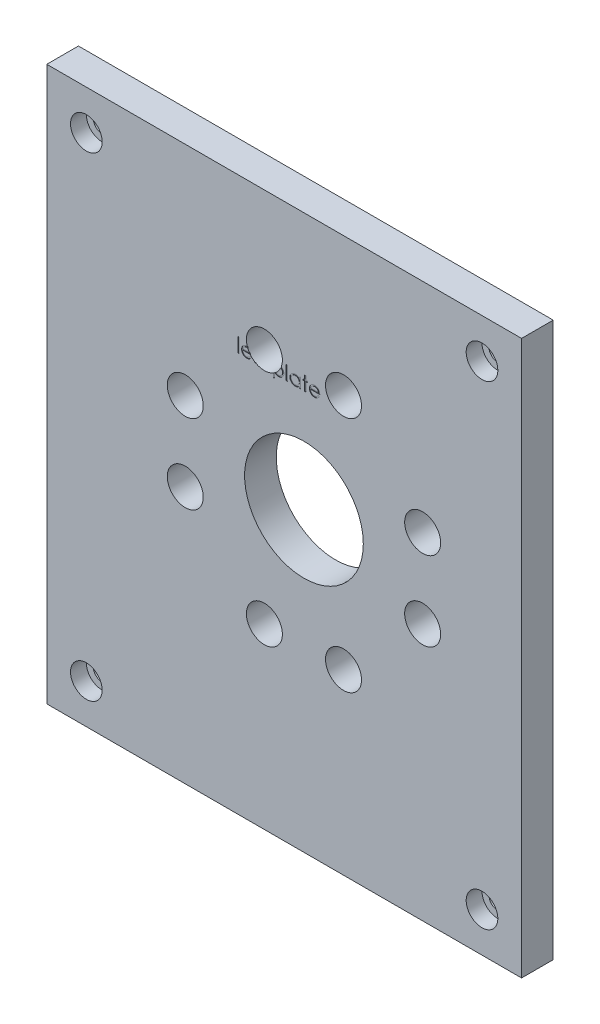
SolidWorks part; units mm, degrees
ref_plane "정면" through (0, 0, 0) normal (0, 0, 1) x (1, 0, 0)
ref_plane "윗면" through (0, 0, 0) normal (0, 1, 0) x (1, 0, 0)
ref_plane "우측면" through (0, 0, 0) normal (1, 0, 0) x (0, 0, -1)
sketch "스케치1" plane through (0, 0, 0) normal (0, 0, 1) x (1, 0, 0)
  line L1 (-60, 70) -> (60, 70)
  line L2 (-60, 70) -> (-60, -70)
  line L3 (-60, -70) -> (60, -70)
  line L4 (60, 70) -> (60, -70)
  line L5 (-60, 70) -> (60, -70) construction
  line L6 (-60, -70) -> (60, 70) construction
  point P0 (0, 0)
  dimension "D1" = 140
  dimension "D2" = 120
extrude "보스-돌출1" add sketch "스케치1" along normal blind 8
hole_wizard "M4 소켓 머리 캡 나사용 카운터보어1" positions "스케치2" profile "스케치3" counterbore size "M4" standard "KS" end condition through all
sketch "스케치2" plane through (0, 0, 8) normal (0, 0, 1) x (1, 0, 0)
  line L0 (60, 70) -> (-60, 70) construction
  line L1 (-60, 70) -> (-60, -70) construction
  line L2 (60, -70) -> (60, 70) construction
  line L3 (-60, -70) -> (60, -70) construction
  point P0 (-50, 60)
  point P7 (50, 60)
  point P9 (50, -60)
  point P11 (-50, -60)
  dimension "D1" = 10
  dimension "D2" = 10
  dimension "D3" = 10
  dimension "D4" = 10
  dimension "D5" = 10
  dimension "D6" = 10
  dimension "D7" = 10
  dimension "D8" = 10
sketch "스케치3" plane through (-50, 60, 8) normal (1, 0, 0) x (0, -1, 0)
  line L0 (0, 0) -> (0, 8)
  line L1 (0, 8) -> (2.25, 8)
  line L3 (2.25, 8) -> (2.25, 4)
  line L4 (2.25, 4) -> (4, 4)
  line L5 (4, 4) -> (4, 0)
  line L7 (4, 0) -> (0, 0)
  line L11 (0, -6.35) -> (0, 107.95) construction
  dimension "관통 구멍 지름" = 4.5
  dimension "관통 구멍 깊이" = 8
  dimension "카운터보어 지름" = 8
  dimension "카운터보어 깊이" = 4
sketch "스케치4" plane through (0, 0, 8) normal (0, 0, 1) x (1, 0, 0)
  line L0 (-59.1569, 30.9963) -> (56.4191, 30.9963) construction
  text T0 "left-plate"
extrude "컷-돌출1" cut sketch "스케치4" against normal blind 0.1
sketch "스케치5" plane through (0, 0, 8) normal (0, 0, 1) x (1, 0, 0)
  line L0 (60, 70) -> (-60, 70) construction
  line L1 (-60, 70) -> (-60, -70) construction
  circle A0 centre (5, 5) radius 15
  dimension "D1" = 30
  dimension "D2" = 65
  dimension "D3" = 65
extrude "컷-돌출2" cut sketch "스케치5" against normal through all
sketch "스케치6" plane through (0, 0, 8) normal (0, 0, 1) x (1, 0, 0)
  circle A2 centre (35, 15) radius 4.55
  circle A3 centre (35, -5) radius 4.55
  circle A4 centre (5, 5) radius 15 construction
  dimension "D1" = 10
  dimension "D3" = 30
  dimension "D4" = 10
  dimension "D5" = 9.1
  dimension "D6" = 9.1
  dimension "D2" = 30
extrude "컷-돌출3" cut sketch "스케치6" against normal through all
pattern_circular "원형 패턴1" count 4 over 360 about axis through (5, 5, 0) along (0, 0, 1) of "컷-돌출3"
